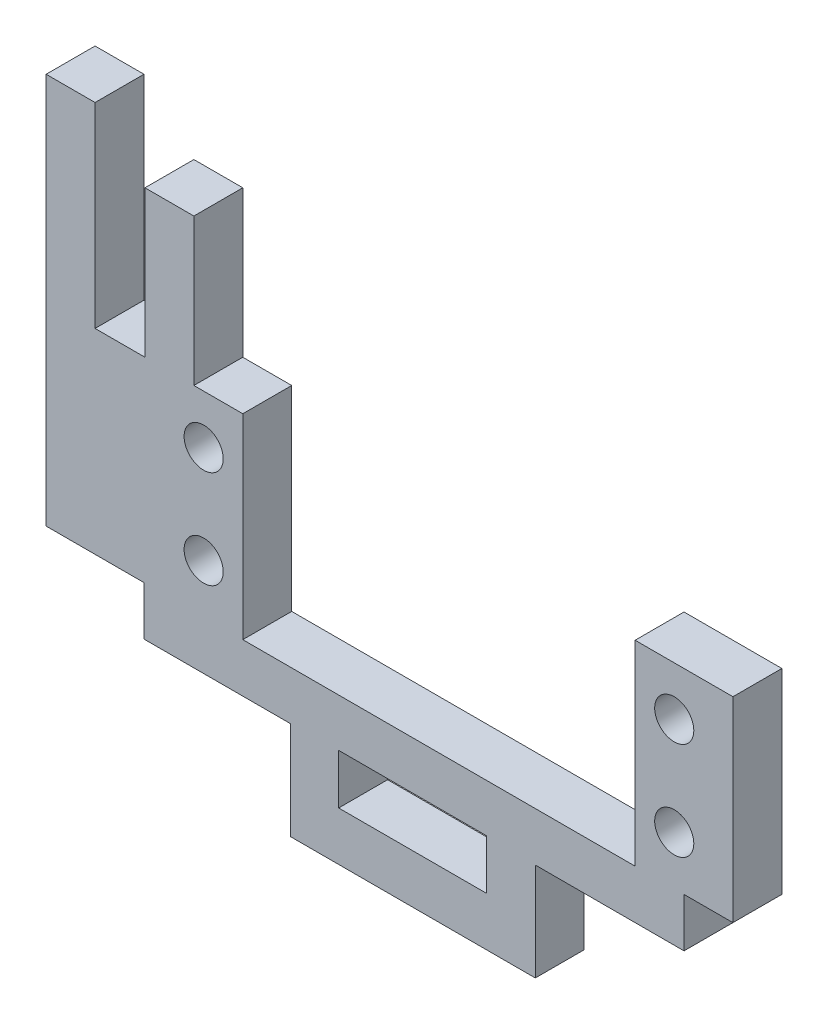
SolidWorks part; units mm, degrees
ref_plane "Front Plane" through (0, 0, 0) normal (0, 0, 1) x (1, 0, 0)
ref_plane "Top Plane" through (0, 0, 0) normal (0, 1, 0) x (1, 0, 0)
ref_plane "Right Plane" through (0, 0, 0) normal (1, 0, 0) x (0, 0, -1)
sketch "Sketch1" plane through (0, 0, 0) normal (0, 0, 1) x (1, 0, 0)
  line L0 (-70.2, 20) -> (-65.2, 20)
  line L1 (-65.2, 20) -> (-65.2, 0)
  line L2 (-65.2, 0) -> (-60.1, 0)
  line L3 (-60.1, 0) -> (-60.1, 15)
  line L4 (-60.1, 15) -> (-55.1, 15)
  line L5 (-55.1, 15) -> (-55.1, 0)
  line L6 (-55.1, 0) -> (-50.1, 0)
  line L7 (-50.1, 0) -> (-50.1, -20)
  line L8 (-50.1, -20) -> (-10, -20)
  line L9 (-10, -20) -> (-10, 0)
  line L10 (-10, 0) -> (0, 0)
  line L11 (0, 0) -> (0, -20)
  line L12 (-5, -25) -> (-20.2, -25)
  line L13 (-20.2, -25) -> (-20.2, -35)
  line L14 (-20.2, -35) -> (-45.2, -35)
  line L15 (-45.2, -35) -> (-45.2, -25)
  line L16 (-45.2, -25) -> (-60.2, -25)
  line L17 (-70.2, -20) -> (-70.2, 20)
  line L18 (-70.2, -20) -> (-60.2, -20)
  line L19 (-40.3, -24.9) -> (-25.2, -24.9)
  line L20 (-40.3, -24.9) -> (-40.3, -30)
  line L21 (-40.3, -30) -> (-25.2, -30)
  line L22 (-25.2, -24.9) -> (-25.2, -30)
  line L23 (-40.3, -24.9) -> (-25.2, -30) construction
  line L24 (-40.3, -30) -> (-25.2, -24.9) construction
  line L25 (-60.2, -20) -> (-60.2, -25)
  line L26 (0, -20) -> (-5, -20)
  line L27 (-5, -20) -> (-5, -25)
  circle A0 centre (-54.1, -5) radius 2
  circle A1 centre (-54.1, -15) radius 2
  circle A2 centre (-6, -5) radius 2
  circle A3 centre (-6, -15) radius 2
  point P2 (-32.75, -27.45)
  dimension "D21" = 4
  dimension "D22" = 4
  dimension "D27" = 4
  dimension "D28" = 4
  dimension "D31" = 5
  dimension "D32" = 5
  dimension "D1" = 5
  dimension "D2" = 5
  dimension "D3" = 5.1
  dimension "D4" = 10
  dimension "D5" = 5
  dimension "D6" = 25
  dimension "D7" = 20
  dimension "D8" = 20
  dimension "D9" = 5
  dimension "D10" = 15
  dimension "D11" = 15
  dimension "D12" = 10
  dimension "D14" = 5
  dimension "D15" = 5
  dimension "D16" = 15
  dimension "D17" = 15.1
  dimension "D18" = 5.1
  dimension "D19" = 5
  dimension "D20" = 5
  dimension "D23" = 5
  dimension "D24" = 5
  dimension "D25" = 4
  dimension "D26" = 4
  dimension "D29" = 4
  dimension "D30" = 4
extrude "Boss-Extrude1" add sketch "Sketch1" along normal blind 5
